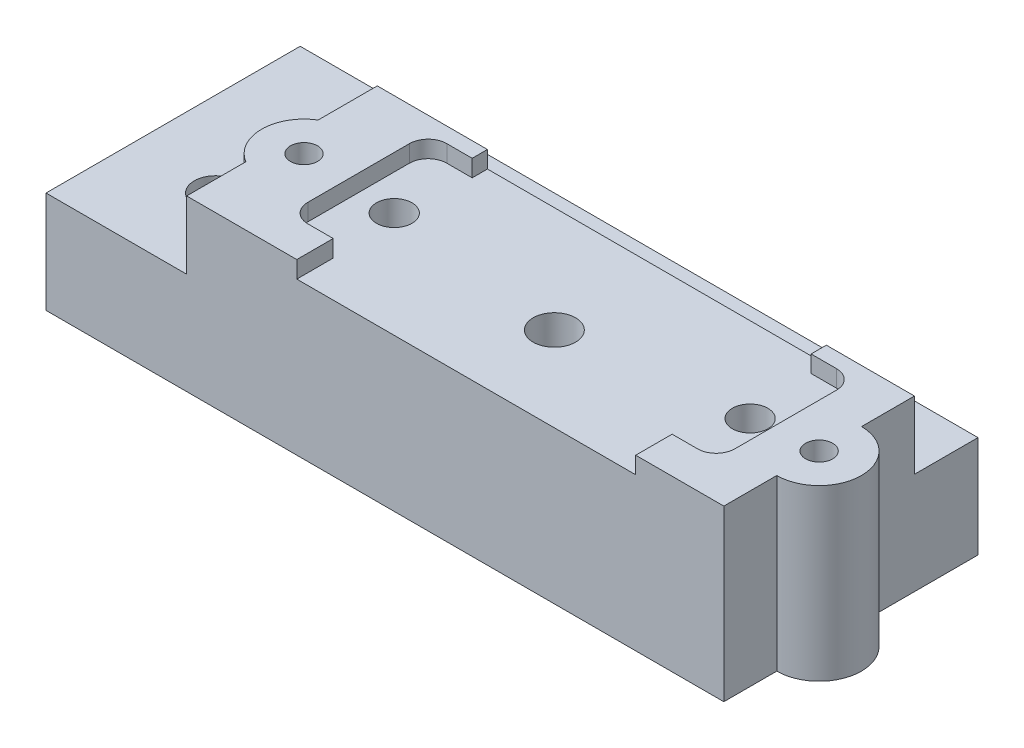
SolidWorks part; units mm, degrees
material "6061 合金"
ref_plane "前视基准面" through (0, 0, 0) normal (0, 0, 1) x (1, 0, 0)
ref_plane "上视基准面" through (0, 0, 0) normal (0, 1, 0) x (1, 0, 0)
ref_plane "右视基准面" through (0, 0, 0) normal (1, 0, 0) x (0, 0, -1)
other "Configuration Table"
sketch "草图1" plane through (0, 0, 0) normal (0, 1, 0) x (1, 0, 0)
  line L1 (-20, -7.5) -> (20, -7.5)
  line L2 (-20, -7.5) -> (-20, 7.5)
  line L3 (-20, 7.5) -> (20, 7.5)
  line L4 (20, -7.5) -> (20, 7.5)
  line L5 (-20, -7.5) -> (20, 7.5) construction
  line L6 (-20, 7.5) -> (20, -7.5) construction
  point P0 (0, 0)
  dimension "D1" = 15
  dimension "D2" = 40
extrude "凸台-拉伸1" add sketch "草图1" along normal blind 6
sketch "草图2" plane through (0, 6, 0) normal (0, 1, 0) x (1, 0, 0)
  line L0 (20, 7.5) -> (-20, 7.5) construction
  line L1 (-6.7, 2.75) -> (16.3, 2.75)
  line L2 (-7.7, 1.75) -> (-7.7, -4.25)
  line L3 (-6.7, -5.25) -> (16.3, -5.25)
  line L4 (17.3, 1.75) -> (17.3, -4.25)
  line L5 (20, -7.5) -> (20, 7.5) construction
  line L6 (-11.7, -7.5) -> (20, -7.5)
  line L7 (-20, -7.5) -> (20, -7.5) construction
  line L8 (20, -7.5) -> (20, 3.75)
  line L9 (20, 3.75) -> (-11.7, 3.75)
  line L10 (-11.7, 3.75) -> (-11.7, -7.5)
  arc A0 (16.3, -5.25) -> (17.3, -4.25) centre (16.3, -4.25) ccw
  arc A1 (16.3, 2.75) -> (17.3, 1.75) centre (16.3, 1.75) cw
  arc A2 (-7.7, -4.25) -> (-6.7, -5.25) centre (-6.7, -4.25) ccw
  arc A3 (-6.7, 2.75) -> (-7.7, 1.75) centre (-6.7, 1.75) ccw
  dimension "D2" = 1
  dimension "D1" = 4.75
  dimension "D3" = 25
  dimension "D4" = 8
  dimension "D5" = 2.7
  dimension "D6" = 1
  dimension "D7" = 4
extrude "凸台-拉伸2" add sketch "草图2" along normal blind 4
sketch "草图3" plane through (0, 6, 0) normal (0, 1, 0) x (1, 0, 0)
  line L4 (-6.7, -5.25) -> (16.3, -5.25)
  line L5 (17.3, -4.25) -> (17.3, 1.75)
  line L6 (16.3, 2.75) -> (-6.7, 2.75)
  line L7 (-7.7, 1.75) -> (-7.7, -4.25)
  line L8 (-6.7, -5.25) -> (16.3, -5.25)
  line L9 (17.3, -4.25) -> (17.3, 1.75)
  line L10 (16.3, 2.75) -> (-6.7, 2.75)
  line L11 (-7.7, 1.75) -> (-7.7, -4.25)
  arc A4 (16.3, -5.25) -> (17.3, -4.25) centre (16.3, -4.25) ccw
  arc A5 (17.3, 1.75) -> (16.3, 2.75) centre (16.3, 1.75) ccw
  arc A6 (-6.7, 2.75) -> (-7.7, 1.75) centre (-6.7, 1.75) ccw
  arc A7 (-7.7, -4.25) -> (-6.7, -5.25) centre (-6.7, -4.25) ccw
  arc A8 (16.3, -5.25) -> (17.3, -4.25) centre (16.3, -4.25) ccw
  arc A9 (17.3, 1.75) -> (16.3, 2.75) centre (16.3, 1.75) ccw
  arc A10 (-6.7, 2.75) -> (-7.7, 1.75) centre (-6.7, 1.75) ccw
  arc A11 (-7.7, -4.25) -> (-6.7, -5.25) centre (-6.7, -4.25) ccw
  dimension "D1" = 0
extrude "凸台-拉伸3" add sketch "草图3" along normal blind 3
sketch "草图4" plane through (0, 10, 0) normal (0, 1, 0) x (1, 0, 0)
  line L0 (20, 3.75) -> (-11.7, 3.75) construction
  line L1 (-5.2, 3.75) -> (14.8, 3.75)
  line L2 (-5.2, 3.75) -> (-5.2, 2.75)
  line L3 (-5.2, 2.75) -> (14.8, 2.75)
  line L4 (14.8, 3.75) -> (14.8, 2.75)
  line L5 (16.3, 2.75) -> (-6.7, 2.75) construction
  line L6 (4.8, 2.75) -> (4.8, -5.25) construction
  line L7 (-6.7, -5.25) -> (16.3, -5.25) construction
  line L8 (4.8, -1.25) -> (-1.4747, -1.25) construction
  line L13 (-11.7, -7.5) -> (20, -7.5) construction
  line L14 (-5.2, -5.25) -> (14.8, -5.25)
  line L15 (-5.2, -5.25) -> (-5.2, -7.5)
  line L16 (-5.2, -7.5) -> (14.8, -7.5)
  line L17 (14.8, -5.25) -> (14.8, -7.5)
  dimension "D1" = 20
extrude "切除-拉伸1" cut sketch "草图4" against normal up to surface (1 mm away) up to face at (4.8, 9, 1.25)
sketch "草图6" plane through (0, 9, 0) normal (0, 1, 0) x (1, 0, 0)
  line L0 (-7.7, -1.25) -> (17.3, -1.25) construction
  line L1 (-7.7, 1.75) -> (-7.7, -4.25) construction
  line L2 (17.3, -4.25) -> (17.3, 1.75) construction
  line L3 (4.8, -1.25) -> (4.8, -9.9294) construction
  circle A0 centre (-5.7, -1.25) radius 1.05
  circle A2 centre (15.3, -1.25) radius 1.05
  dimension "D2" = 2.1
  dimension "D1" = 21
extrude "切除-拉伸2" cut sketch "草图6" against normal through all
sketch "草图7" plane through (0, 0, 0) normal (0, -1, 0) x (1, 0, 0)
  circle A0 centre (-5.7, 1.25) radius 2
  circle A1 centre (15.3, 1.25) radius 2
  dimension "D1" = 4
extrude "切除-拉伸3" cut sketch "草图7" against normal blind 2.1
sketch "草图8" plane through (0, 0, 0) normal (0, -1, 0) x (1, 0, 0)
  line L0 (-20, 2.5) -> (5, 2.5) construction
  line L1 (-20, -7.5) -> (-20, 7.5) construction
  line L3 (-20, 7.5) -> (20, 7.5) construction
  circle A0 centre (-15, 2.5) radius 1.25
  circle A1 centre (5, 2.5) radius 1.25
  dimension "D1" = 2.5
  dimension "D2" = 5
  dimension "D3" = 25
  dimension "D4" = 5
extrude "切除-拉伸4" cut sketch "草图8" against normal through all
cosmetic thread "装饰螺纹线1" parameters "D2"=3
cosmetic thread "装饰螺纹线2" parameters "D1"=5, "D2"=3
sketch "草图9" plane through (0, 0, 0) normal (0, 1, 0) x (1, 0, 0)
  line L0 (20, -7.5) -> (20, 3.75) construction
  line L1 (4.8, -7.5) -> (4.8, 3.75) construction
  line L2 (14.8, -7.5) -> (-5.2, -7.5) construction
  line L3 (-5.2, 3.75) -> (14.8, 3.75) construction
  circle A0 centre (20, -1.875) radius 2.5
  circle A1 centre (-10.4, -1.875) radius 2.5
  dimension "D1" = 5
extrude "凸台-拉伸4" add sketch "草图9" along normal blind 10
sketch "草图10" plane through (0, 10, 0) normal (0, 1, 0) x (1, 0, 0)
  circle A0 centre (-10.4, -1.875) radius 0.8
  circle A1 centre (20, -1.875) radius 0.8
  dimension "D1" = 1.6
extrude "切除-拉伸5" cut sketch "草图10" against normal through all
cosmetic thread "装饰螺纹线3" parameters "D2"=2
cosmetic thread "装饰螺纹线4" parameters "D2"=2
sketch "草图11" plane through (0, 10, 0) normal (0, 1, 0) x (1, 0, 0)
  line L0 (17.3, 1.75) -> (17.3, -4.25) construction
  line L1 (-6.7, 2.75) -> (16.3, 2.75) construction
  line L2 (-6.7, -5.25) -> (16.3, -5.25) construction
  line L3 (-7.7, 1.75) -> (-7.7, -4.25) construction
  line L4 (17.3, 1.75) -> (17.3, -4.25) construction
  line L5 (-6.7, 2.75) -> (16.3, 2.75) construction
  line L6 (-6.7, -5.25) -> (16.3, -5.25) construction
  line L7 (-7.7, 1.75) -> (-7.7, -4.25) construction
  line L8 (17.4, 1.75) -> (17.4, -4.25)
  line L9 (-6.7, 2.85) -> (16.3, 2.85)
  line L10 (-7.8, 1.75) -> (-7.8, -4.25)
  line L11 (-6.7, -5.35) -> (16.3, -5.35)
  arc A0 (16.3, -5.25) -> (17.3, -4.25) centre (16.3, -4.25) ccw construction
  arc A1 (17.3, 1.75) -> (16.3, 2.75) centre (16.3, 1.75) ccw construction
  arc A2 (-6.7, 2.75) -> (-7.7, 1.75) centre (-6.7, 1.75) ccw construction
  arc A3 (-7.7, -4.25) -> (-6.7, -5.25) centre (-6.7, -4.25) ccw construction
  arc A4 (16.3, -5.25) -> (17.3, -4.25) centre (16.3, -4.25) ccw construction
  arc A5 (17.3, 1.75) -> (16.3, 2.75) centre (16.3, 1.75) ccw construction
  arc A6 (-6.7, 2.75) -> (-7.7, 1.75) centre (-6.7, 1.75) ccw construction
  arc A7 (-7.7, -4.25) -> (-6.7, -5.25) centre (-6.7, -4.25) ccw construction
  arc A8 (16.3, -5.35) -> (17.4, -4.25) centre (16.3, -4.25) ccw
  arc A9 (17.4, 1.75) -> (16.3, 2.85) centre (16.3, 1.75) ccw
  arc A10 (-6.7, 2.85) -> (-7.8, 1.75) centre (-6.7, 1.75) ccw
  arc A11 (-7.8, -4.25) -> (-6.7, -5.35) centre (-6.7, -4.25) ccw
  dimension "D1" = 0.1
extrude "切除-拉伸6" cut sketch "草图11" against normal blind 1
sketch "草图13" plane through (0, 0, 0) normal (0, -1, 0) x (1, 0, 0)
  line L0 (-20, -4.5) -> (-15, -4.5) construction
  line L1 (-20, -7.5) -> (-20, 7.5) construction
  line L2 (20, -7.5) -> (-20, -7.5) construction
  line L3 (-15, -4.5) -> (-5, -4.5) construction
  circle A0 centre (-15, -4.5) radius 2.75
  circle A1 centre (-5, -4.5) radius 2.75
  circle A2 centre (5, -4.5) radius 2.75
  circle A3 centre (15, -4.5) radius 2.75
  dimension "D3" = 5.5
  dimension "D1" = 5
  dimension "D2" = 3
  dimension "D5" = 10
  dimension "D4" = 4
extrude "切除-拉伸8" cut sketch "草图13" against normal blind 3.1
